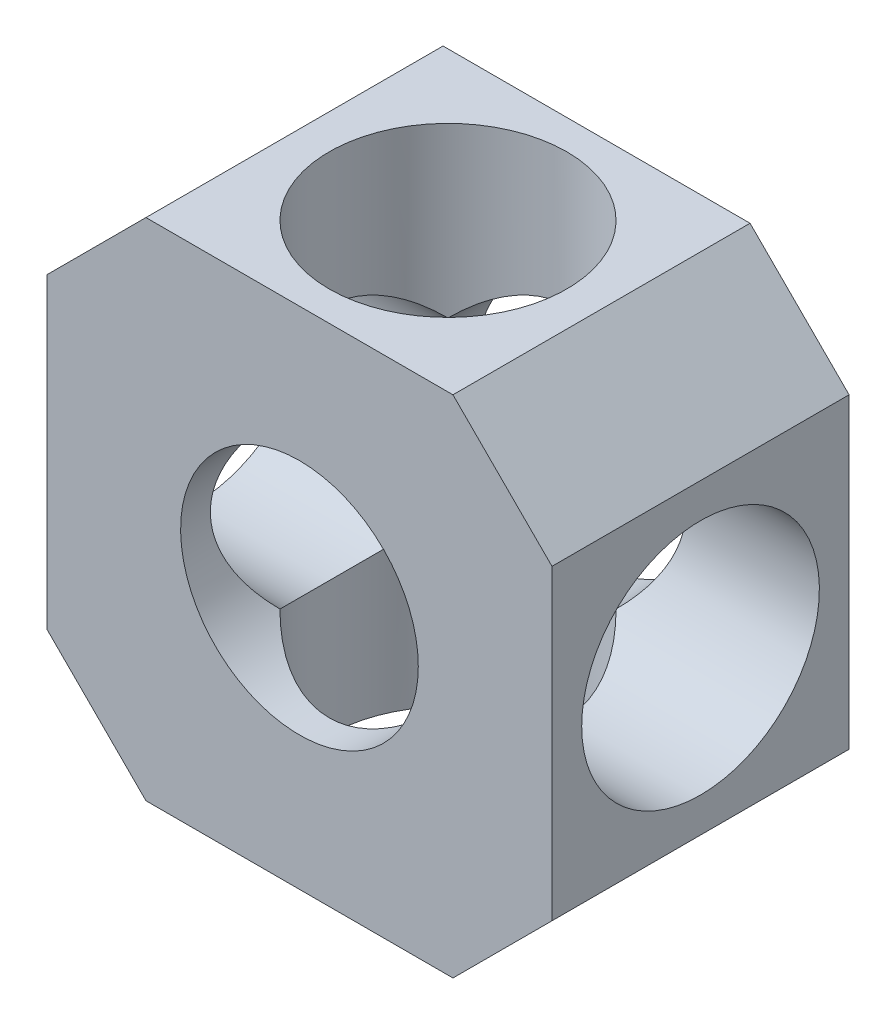
SolidWorks part; units mm, degrees
ref_plane "Front Plane" through (0, 0, 0) normal (0, 0, 1) x (1, 0, 0)
ref_plane "Top Plane" through (0, 0, 0) normal (0, 1, 0) x (1, 0, 0)
ref_plane "Right Plane" through (0, 0, 0) normal (1, 0, 0) x (0, 0, -1)
sketch "Sketch1" plane through (0, 0, 0) normal (0, 0, 1) x (1, 0, 0)
  line L0 (-12.75, 7.75) -> (-7.75, 12.75)
  line L1 (-7.75, 12.75) -> (7.75, 12.75)
  line L2 (-12.75, 7.75) -> (-12.75, -7.75)
  line L3 (-7.75, -12.75) -> (7.75, -12.75)
  line L4 (12.75, 7.75) -> (12.75, -7.75)
  line L5 (7.75, 12.75) -> (12.75, 7.75)
  line L6 (7.75, -12.75) -> (12.75, -7.75)
  line L7 (-12.75, -7.75) -> (-7.75, -12.75)
  circle A0 centre (0, 0) radius 6
  point P0 (-12.75, 12.75)
  point P1 (12.75, -12.75)
  point P2 (-12.75, -12.75)
  point P3 (12.75, 12.75)
  dimension "D3" = 12
  dimension "D1" = 25.5
  dimension "D2" = 25.5
extrude "Boss-Extrude1" add sketch "Sketch1" along normal mid plane 15
sketch "Sketch3" plane through (0, 12.75, 0) normal (0, 1, 0) x (1, 0, 0)
  circle A0 centre (0, 0) radius 6
  dimension "D1" = 12
extrude "Cut-Extrude1" cut sketch "Sketch3" against normal through all
pattern_circular "CirPattern1" count 4 over 360 about axis through (0, 0, 7.5) along (0, 0, -1) of "Cut-Extrude1"
scale "Scale1" scale about centroid uniform scaling yes scale factor 0.828947
